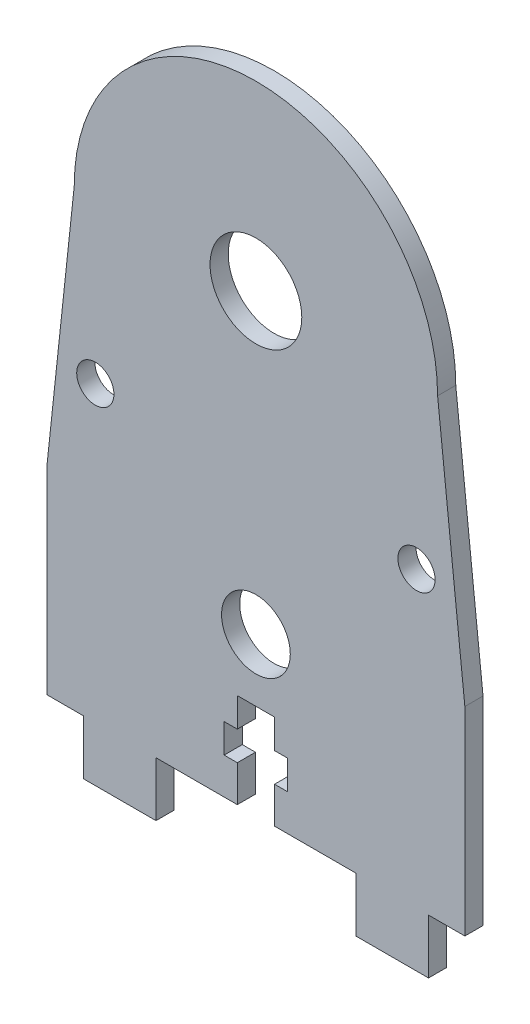
SolidWorks part; units mm, degrees
ref_plane "前视基准面" through (0, 0, 0) normal (0, 0, 1) x (1, 0, 0)
ref_plane "上视基准面" through (0, 0, 0) normal (0, 1, 0) x (1, 0, 0)
ref_plane "右视基准面" through (0, 0, 0) normal (1, 0, 0) x (0, 0, -1)
sketch "草图1" plane through (0, 0, 0) normal (0, 0, 1) x (1, 0, 0)
  line L0 (-7.6377, 70.7363) -> (-7.6377, -1.0167) construction
  line L1 (-48.6877, 85.7363) -> (33.4123, 85.7363) construction
  line L2 (-5.5877, 20.7363) -> (-5.5877, 24.7363)
  line L5 (-5.5877, 24.7363) -> (-4.1377, 24.7363)
  line L6 (-4.1377, 24.7363) -> (-4.1377, 27.9363)
  line L10 (-7.6377, 70.7363) -> (29.2367, 33.8619) construction
  line L11 (-4.1377, 27.9363) -> (-5.5877, 27.9363)
  line L12 (-5.5877, 27.9363) -> (-5.5877, 31.1363)
  line L13 (-5.5877, 31.1363) -> (-9.6877, 31.1363)
  line L15 (3.3623, 20.7363) -> (3.3623, 14.7363)
  line L16 (3.3623, 14.7363) -> (11.3623, 14.7363)
  line L17 (11.3623, 14.7363) -> (11.3623, 20.7363)
  line L18 (7.3623, 14.7363) -> (7.3623, 20.7363) construction
  line L19 (11.3623, 20.7363) -> (-5.5877, 20.7363) construction
  line L20 (-5.5877, 20.7363) -> (3.3623, 20.7363)
  line L21 (11.3623, 20.7363) -> (15.3623, 20.7363)
  line L22 (15.3623, 42.6223) -> (12.3623, 70.7363)
  line L23 (15.3623, 42.6223) -> (15.3623, 20.7363)
  line L24 (-30.6377, 42.6223) -> (-27.6377, 70.7363)
  line L25 (-26.6377, 20.7363) -> (-9.6877, 20.7363) construction
  line L26 (-22.6377, 14.7363) -> (-22.6377, 20.7363) construction
  line L27 (-30.6377, 42.6223) -> (-30.6377, 20.7363)
  line L28 (-26.6377, 20.7363) -> (-30.6377, 20.7363)
  line L29 (-9.6877, 20.7363) -> (-18.6377, 20.7363)
  line L30 (-26.6377, 14.7363) -> (-26.6377, 20.7363)
  line L31 (-18.6377, 14.7363) -> (-26.6377, 14.7363)
  line L32 (-18.6377, 20.7363) -> (-18.6377, 14.7363)
  line L33 (-9.6877, 27.9363) -> (-9.6877, 31.1363)
  line L34 (-11.1377, 27.9363) -> (-9.6877, 27.9363)
  line L35 (-11.1377, 24.7363) -> (-11.1377, 27.9363)
  line L36 (-9.6877, 24.7363) -> (-11.1377, 24.7363)
  line L37 (-9.6877, 20.7363) -> (-9.6877, 24.7363)
  circle A0 centre (-7.6377, 70.7363) radius 5.05
  circle A1 centre (-7.6377, 70.7363) radius 25 construction
  circle A4 centre (-7.6377, 70.7363) radius 20 construction
  arc A5 (12.3623, 70.7363) -> (-27.6377, 70.7363) centre (-7.6377, 70.7363) ccw
  circle A8 centre (10.0399, 53.0586) radius 2.05
  circle A9 centre (-25.3154, 53.0586) radius 2.05
  circle A10 centre (-7.6377, 38.0045) radius 3.7839
  point P39 (-7.6377, 31.1363)
  dimension "D1" = 10.1
  dimension "D2" = 50
  dimension "D3" = 4.1
  dimension "D4" = 15
  dimension "D5" = 3.2
  dimension "D6" = 4
  dimension "D7" = 2.05
  dimension "D8" = 3.5
  dimension "D9" = 15
  dimension "D10" = 6
  dimension "D11" = 4
  dimension "D12" = 45
  dimension "D13" = 8
  dimension "D14" = 50
extrude "凸台-拉伸1" add sketch "草图1" along normal blind 2
sketch "草图2" plane through (0, 20.7363, 0) normal (0, -1, 0) x (1, 0, 0)
  line L0 (-9.6877, 1) -> (-5.5877, 1) construction
  line L1 (-9.6877, 2) -> (-9.6877, 0) construction
  line L2 (-5.5877, 2) -> (-5.5877, 0) construction
  circle A0 centre (-7.6377, 1) radius 2.05
